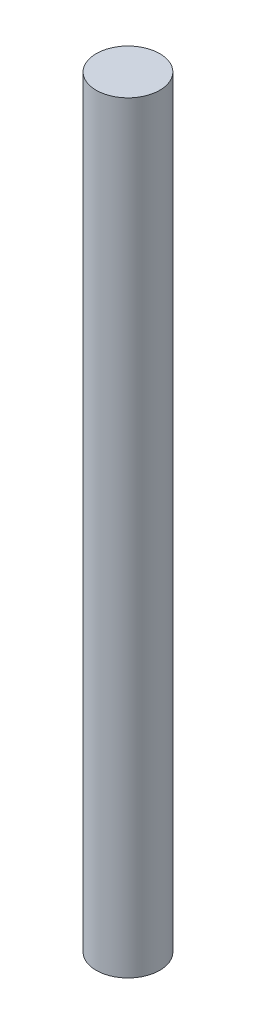
SolidWorks part; units mm, degrees
ref_plane "Front Plane" through (0, 0, 0) normal (0, 0, 1) x (1, 0, 0)
ref_plane "Top Plane" through (0, 0, 0) normal (0, 1, 0) x (1, 0, 0)
ref_plane "Right Plane" through (0, 0, 0) normal (1, 0, 0) x (0, 0, -1)
sketch "Sketch3" plane through (0, 0, 0) normal (0, 0, 1) x (1, 0, 0)
  line L0 (0, 0) -> (2.7, 0)
  line L1 (0, 17) -> (3.35, 17)
  line L2 (3.35, 17) -> (2.7, 0)
  line L3 (0, 17) -> (0, 0)
  dimension "D1" = 3.35
  dimension "D2" = 2.7
  dimension "D3" = 17
revolve "Revolve1" add sketch "Sketch3" angle 360 about L3
sketch "Sketch4" plane through (0, 0, 0) normal (0, 1, 0) x (1, 0, 0)
  circle A0 centre (0, 0) radius 5
  dimension "D1" = 10
extrude "Boss-Extrude1" add sketch "Sketch4" along normal blind 120
sketch "Sketch5" plane through (0, 0, 0) normal (0, 0, 1) x (1, 0, 0)
  line L1 (0, 17) -> (0, 0)
  line L4 (0, 0) -> (3.35, 0)
  line L5 (-5, 0) -> (5, 0) construction
  line L6 (3.35, 0) -> (3.35, 17)
  line L7 (3.35, 17) -> (0, 17)
  point P12 (0, 0)
  point P13 (9.7896, 17)
  dimension "D1" = 3.35
  dimension "D2" = 3.35
revolve "Cut-Revolve1" cut sketch "Sketch5" angle 360 about L1
